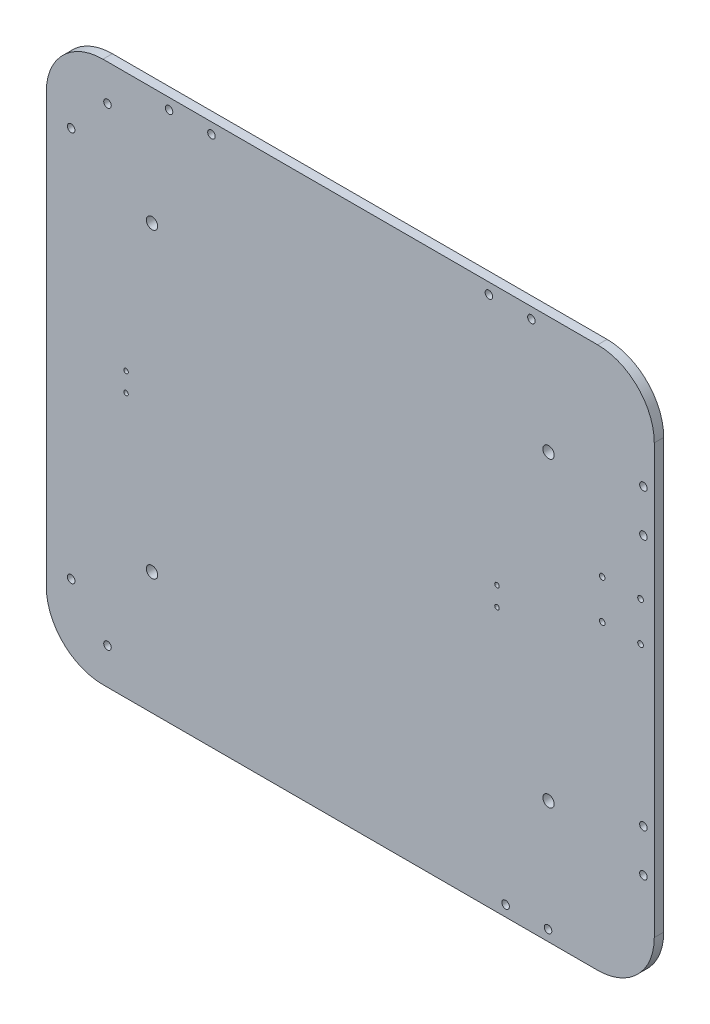
SolidWorks part; units mm, degrees
ref_plane "Front Plane" through (0, 0, 0) normal (0, 0, 1) x (1, 0, 0)
ref_plane "Top Plane" through (0, 0, 0) normal (0, 1, 0) x (1, 0, 0)
ref_plane "Right Plane" through (0, 0, 0) normal (1, 0, 0) x (0, 0, -1)
sketch "Sketch1" plane through (0, 0, 0) normal (0, 0, 1) x (1, 0, 0)
  line L0 (-26, -224.7) -> (236, -224.7)
  line L1 (105, 65) -> (105, 114.8128) construction
  line L2 (-60, -81.25) -> (105.0047, -81.25) construction
  line L30 (-60, 35) -> (-60, -20) construction
  line L31 (270, 35) -> (270, -20) construction
  line L48 (266, -194.7) -> (266, 32.2)
  line L49 (236, 62.2) -> (-26, 62.2)
  line L54 (-56, 32.2) -> (-56, -194.7)
  line L55 (-30, -227.5) -> (240, -227.5) construction
  line L56 (240, 65) -> (176.564, 65) construction
  arc A0 (-26, -224.7) -> (-56, -194.7) centre (-26, -194.7) cw
  arc A1 (236, -224.7) -> (266, -194.7) centre (236, -194.7) ccw
  arc A3 (266, 32.2) -> (236, 62.2) centre (236, 32.2) ccw
  arc A5 (-26, 62.2) -> (-56, 32.2) centre (-26, 32.2) ccw
  circle A7 centre (238.4253, -63.7) radius 1.5
  circle A9 centre (258.7253, -63.7) radius 1.5
  circle A11 centre (258.7253, -43) radius 1.5
  circle A13 centre (238.4253, -43) radius 1.5
  circle A18 centre (210, -160) radius 3
  circle A19 centre (-13.7646, -84.8) radius 1.2
  circle A20 centre (210, 0) radius 3
  circle A21 centre (-13.7646, -74.7) radius 1.2
  circle A22 centre (0, 0) radius 3
  circle A27 centre (182.7, -84.8) radius 1.2
  circle A29 centre (182.7, -74.7) radius 1.2
  circle A36 centre (0, -160) radius 3
  circle A48 centre (260.25, -146.4976) radius 2
  circle A49 centre (260.25, -168.9768) radius 2
  circle A50 centre (260.25, -13.1478) radius 2
  circle A51 centre (260.25, 9.3314) radius 2
  circle A52 centre (200.9167, 56.45) radius 2
  circle A53 centre (178.4375, 56.45) radius 2
  circle A54 centre (31.4877, 56.45) radius 2
  circle A55 centre (9.0084, 56.45) radius 2
  circle A56 centre (-23.5803, 43.0465) radius 2
  circle A57 centre (-42.8183, 22.1272) radius 2
  circle A58 centre (-42.8183, -184.6272) radius 2
  circle A59 centre (-23.5803, -205.5465) radius 2
  circle A60 centre (187.249, -218.95) radius 2
  circle A61 centre (209.7282, -218.95) radius 2
  point P7 (0, 0)
  point P11 (0, 0)
  point P45 (0, 0)
  point P47 (0, 0)
  dimension "D3" = 3
  dimension "D4" = 3
  dimension "D5" = 3
  dimension "D6" = 3
  dimension "D8" = 30
  dimension "D10" = 2.4
  dimension "D11" = 2.4
  dimension "D12" = 2.4
  dimension "D13" = 2.4
  dimension "D1" = 4
  dimension "D2" = 4
  dimension "D7" = 2.8
  dimension "D9" = 2.8
extrude "Boss-Extrude1" add sketch "Sketch1" along normal blind 5
